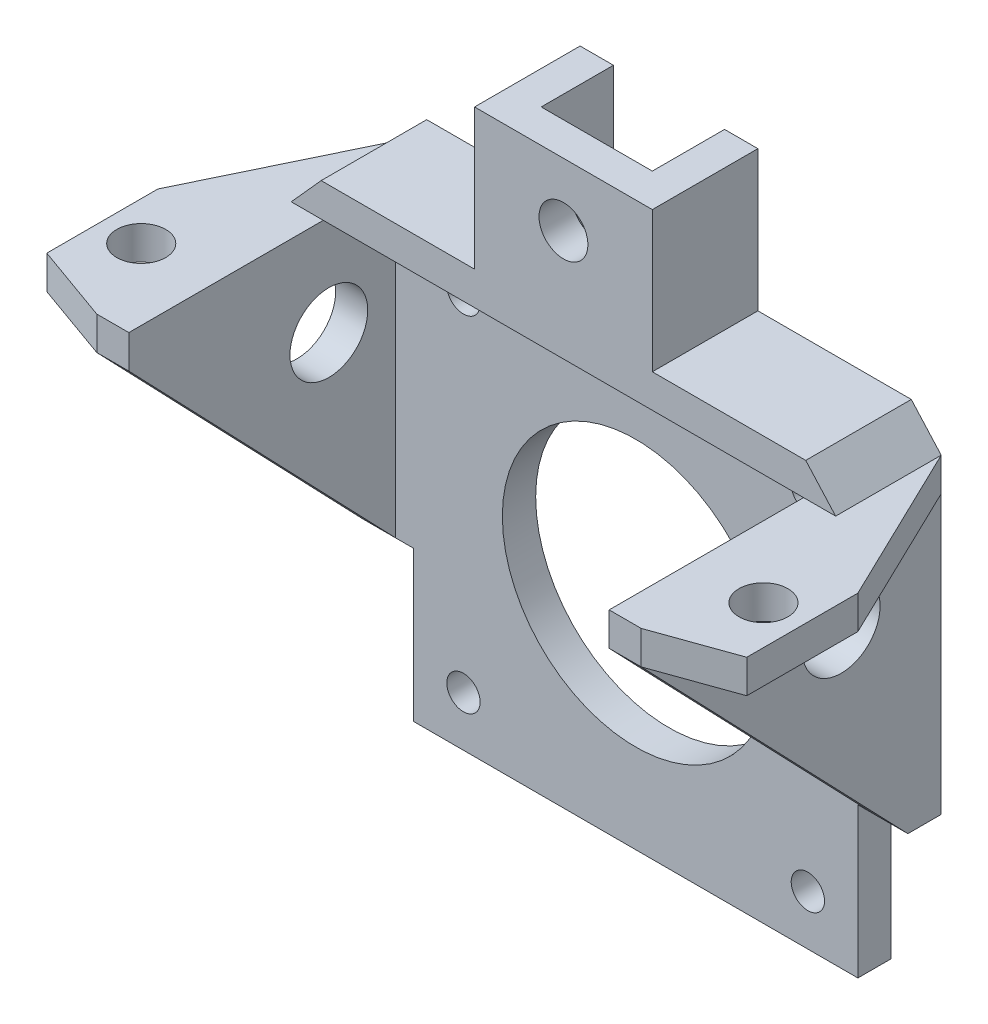
SolidWorks part; units mm, degrees
material "ABS"
ref_plane "Front Plane" through (0, 0, 0) normal (0, 0, 1) x (1, 0, 0)
ref_plane "Top Plane" through (0, 0, 0) normal (0, 1, 0) x (1, 0, 0)
ref_plane "Right Plane" through (0, 0, 0) normal (1, 0, 0) x (0, 0, -1)
sketch "Sketch1" plane through (0, 0, 0) normal (0, 0, 1) x (1, 0, 0)
  line L0 (-8, 22.25) -> (-8, 34.894)
  line L1 (-20, -22.25) -> (20, -22.25)
  line L2 (-20, -22.25) -> (-20, 22.25)
  line L3 (-20, 22.25) -> (-8, 22.25)
  line L4 (20, -22.25) -> (20, 22.25)
  line L5 (-20, -22.25) -> (20, 22.25) construction
  line L6 (-20, 22.25) -> (20, -22.25) construction
  line L7 (-8, 34.894) -> (8, 34.894)
  line L8 (8, 34.894) -> (8, 22.25)
  line L9 (8, 22.25) -> (20, 22.25)
  point P0 (0, 0)
  dimension "D1" = 40
  dimension "D2" = 44.5
  dimension "D3" = 12.644
  dimension "D4" = 16
extrude "Boss-Extrude1" add sketch "Sketch1" along normal blind 3
sketch "Sketch2" plane through (0, 0, 0) normal (0, 0, -1) x (-1, 0, 0)
  line L0 (31.5, 19.25) -> (21.614, 19.25)
  line L1 (21.614, 19.25) -> (21.614, -8.75)
  line L2 (21.614, -8.75) -> (24.5, -8.75)
  line L3 (24.5, -8.75) -> (24.5, 16.25)
  line L4 (24.5, 16.25) -> (31.5, 16.25)
  line L5 (31.5, 16.25) -> (31.5, 19.25)
  line L6 (20, 22.25) -> (20, -22.25) construction
  line L7 (20, -22.25) -> (-20, -22.25) construction
  line L8 (0, -22.25) -> (0, -14.1694) construction
  line L9 (-31.5, 16.25) -> (-31.5, 19.25)
  line L10 (-24.5, 16.25) -> (-31.5, 16.25)
  line L11 (-24.5, -8.75) -> (-24.5, 16.25)
  line L12 (-21.614, -8.75) -> (-24.5, -8.75)
  line L13 (-21.614, 19.25) -> (-21.614, -8.75)
  line L14 (-31.5, 19.25) -> (-21.614, 19.25)
  dimension "D1" = 3
  dimension "D2" = 2.886
  dimension "D3" = 4.5
  dimension "D4" = 13.5
  dimension "D5" = 28
  dimension "D6" = 9.886
extrude "Boss-Extrude2" add sketch "Sketch2" against normal blind 27 separate body
sketch "Sketch3" plane through (0, 0, 0) normal (0, 0, -1) x (-1, 0, 0)
  line L0 (-21.614, -8.75) -> (21.614, -8.75)
  line L1 (21.614, -8.75) -> (21.614, 19.25)
  line L2 (21.614, 19.25) -> (24.5, 19.25)
  line L3 (31.5, 19.25) -> (21.614, 19.25) construction
  line L4 (24.5, 19.25) -> (21.807, 22.25)
  line L5 (21.807, 22.25) -> (-21.807, 22.25)
  line L6 (-21.807, 22.25) -> (-24.5, 19.25)
  line L7 (-21.614, 19.25) -> (-31.5, 19.25) construction
  line L8 (-24.5, 19.25) -> (-21.614, 19.25)
  line L9 (-21.614, 19.25) -> (-21.614, -8.75)
  line L10 (0, 22.25) -> (0, 34.894) construction
  line L11 (-8, 34.894) -> (8, 34.894) construction
  dimension "D1" = 43.614
  dimension "D2" = 49
extrude "Boss-Extrude3" add sketch "Sketch3" against normal up to surface (3 mm away) up to face at (0, 14.286, 3)
sketch "Sketch4" plane through (0, 0, 3) normal (0, 0, 1) x (1, 0, 0)
  line L0 (-24.5, 19.25) -> (-21.807, 22.25)
  line L1 (-21.807, 22.25) -> (-8, 22.25)
  line L2 (-8, 22.25) -> (-8, 34.894)
  line L3 (-8, 34.894) -> (8, 34.894)
  line L4 (8, 34.894) -> (8, 22.25)
  line L5 (8, 22.25) -> (21.807, 22.25)
  line L6 (21.807, 22.25) -> (24.5, 19.25)
  line L7 (24.5, 19.25) -> (-24.5, 19.25)
extrude "Boss-Extrude4" add sketch "Sketch4" along normal blind 6.5
sketch "Sketch5" plane through (24.5, 0, 0) normal (1, 0, 0) x (0, 0, -1)
  line L0 (-27, 16.25) -> (-3, -8.75)
  line L1 (-3, -8.75) -> (-27, -8.75)
  line L2 (-27, -8.75) -> (-27, 16.25)
  line L3 (-27, 19.25) -> (0, 19.25) construction
  line L4 (0, 16.25) -> (0, -8.75) construction
  circle A0 centre (-9, 10.25) radius 3.5
  dimension "D1" = 7
  dimension "D2" = 9
  dimension "D3" = 9
extrude "Cut-Extrude1" cut sketch "Sketch5" against normal through all
sketch "Sketch6" plane through (0, 16.25, 0) normal (0, -1, 0) x (1, 0, 0)
  line L0 (24.5, 27) -> (31.5, 27)
  line L1 (31.5, 27) -> (31.5, 24.5)
  line L2 (31.5, 27) -> (31.5, 0) construction
  line L3 (31.5, 24.5) -> (24.5, 27)
  line L4 (24.5, 0) -> (31.5, 14.5)
  line L5 (31.5, 14.5) -> (31.5, 0)
  line L6 (31.5, 0) -> (24.5, 0)
  line L7 (24.5, 27) -> (21.614, 27) construction
  line L8 (0, 9.5) -> (0, 24.5) construction
  line L9 (-21.614, 9.5) -> (21.614, 9.5) construction
  line L10 (-31.5, 0) -> (-24.5, 0)
  line L11 (-31.5, 14.5) -> (-31.5, 0)
  line L12 (-24.5, 0) -> (-31.5, 14.5)
  line L13 (-31.5, 24.5) -> (-24.5, 27)
  line L14 (-31.5, 27) -> (-31.5, 24.5)
  line L15 (-24.5, 27) -> (-31.5, 27)
  circle A0 centre (28, 19.5) radius 2.2
  circle A1 centre (-28, 19.5) radius 2.2
  dimension "D3" = 4.4
  dimension "D4" = 3.5
  dimension "D5" = 7.5
  dimension "D1" = 14.5
  dimension "D2" = 10
extrude "Cut-Extrude2" cut sketch "Sketch6" against normal through all
sketch "Sketch7" plane through (0, 34.894, 0) normal (0, 1, 0) x (1, 0, 0)
  line L0 (8, 0) -> (-8, 0) construction
  line L1 (-5, 0) -> (5, 0)
  line L2 (-5, 0) -> (-5, -6.5)
  line L3 (-5, -6.5) -> (5, -6.5)
  line L4 (5, 0) -> (5, -6.5)
  line L5 (8, -9.5) -> (8, 0) construction
  line L6 (-8, -9.5) -> (-8, 0) construction
  line L7 (8, -9.5) -> (-8, -9.5) construction
  dimension "D1" = 3
  dimension "D2" = 3
  dimension "D3" = 3
extrude "Cut-Extrude3" cut sketch "Sketch7" against normal up to surface (12.644 mm away) up to face at (-14.9035, 22.25, 4.75)
sketch "Sketch8" plane through (0, 0, 3) normal (0, 0, 1) x (1, 0, 0)
  line L0 (-15.5, 13.25) -> (15.5, 13.25) construction
  line L1 (15.5, 13.25) -> (15.5, -17.75) construction
  line L2 (15.5, -17.75) -> (-15.5, 13.25) construction
  line L3 (-20, -22.25) -> (20, -22.25) construction
  line L4 (0, -2.25) -> (0, -22.25) construction
  circle A0 centre (0, -2.25) radius 12
  circle A1 centre (-15.5, 13.25) radius 1.5
  circle A2 centre (15.5, 13.25) radius 1.5
  circle A3 centre (15.5, -17.75) radius 1.5
  circle A4 centre (-15.5, -17.75) radius 1.5
  dimension "D1" = 3
  dimension "D3" = 24
  dimension "D4" = 20
  dimension "D2" = 31
extrude "Cut-Extrude4" cut sketch "Sketch8" against normal through all
sketch "Sketch9" plane through (0, 0, 9.5) normal (0, 0, 1) x (1, 0, 0)
  line L0 (8, 34.894) -> (-8, 34.894) construction
  line L1 (0, 34.894) -> (0, 29.2509) construction
  circle A0 centre (0, 29.2509) radius 2.2
  dimension "D1" = 4.4
  dimension "D2" = 5.6431
extrude "Cut-Extrude5" cut sketch "Sketch9" against normal through all
